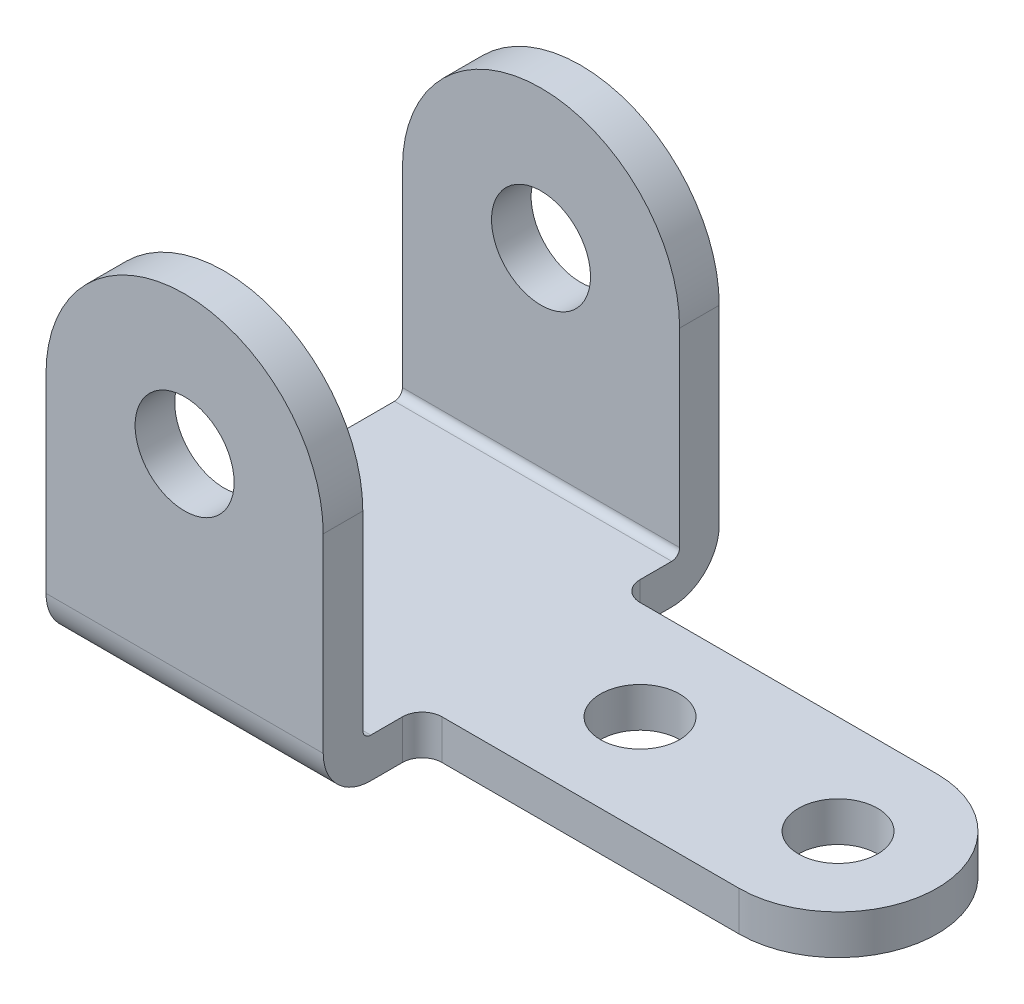
SolidWorks part; units mm, degrees
material "PW20:29:Sc:0:"
ref_plane "Front" through (0, 0, 0) normal (0, 0, 1) x (1, 0, 0)
ref_plane "Top" through (0, 0, 0) normal (0, 1, 0) x (1, 0, 0)
ref_plane "Right" through (0, 0, 0) normal (1, 0, 0) x (0, 0, -1)
sketch "Sketch4" plane through (0, 0, 0) normal (0, 0, 1) x (1, 0, 0)
  line L0 (-35, 0) -> (-35, -60)
  line L1 (-35, -60) -> (35, -60)
  line L2 (35, -60) -> (35, 0)
  arc A0 (35, 0) -> (-35, 0) centre (0, 0) ccw
  dimension "D1" = 35
  dimension "D2" = 60
extrude "\"U\" shape" add sketch "Sketch4" along normal blind 100
fillet "Fillet" radius 12 2 edges at (0, -60, 100) (0, -60, 0)
shell "Thickness" thickness 10
sketch "Sketch8" plane through (0, 0, 100) normal (0, 0, 1) x (1, 0, 0)
  circle A0 centre (0, 0) radius 12.5
  dimension "D1" = 25
extrude "Inner Hole" cut sketch "Sketch8" against normal through all
sketch "Sketch7" plane through (0, -60, 0) normal (0, -1, 0) x (1, 0, 0)
  line L0 (-35, 50) -> (189.435, 50) construction
  line L1 (35, 25) -> (115, 25)
  line L2 (35, 75) -> (115, 75)
  line L3 (35, 25) -> (35, 75)
  line L4 (35, 88) -> (35, 12) construction
  line L5 (-35, 88) -> (-35, 12) construction
  arc A0 (115, 25) -> (115, 75) centre (115, 50) ccw
  dimension "D2" = 25
  dimension "D1" = 80
extrude "Tongue" add sketch "Sketch7" against normal up to surface (10 mm away) up to face at (0, -50, 50)
sketch "Sketch9" plane through (0, -60, 0) normal (0, -1, 0) x (1, 0, 0)
  line L0 (-35, 50) -> (169.8623, 50) construction
  line L1 (-35, 88) -> (-35, 12) construction
  circle A0 centre (65, 50) radius 10
  circle A2 centre (115, 50) radius 10
  dimension "D1" = 20
  dimension "D2" = 50
extrude "Mounting Holes" cut sketch "Sketch9" against normal through all
fillet "Fillet1" radius 5 2 edges at (35, -55, 25) (35, -55, 75)
